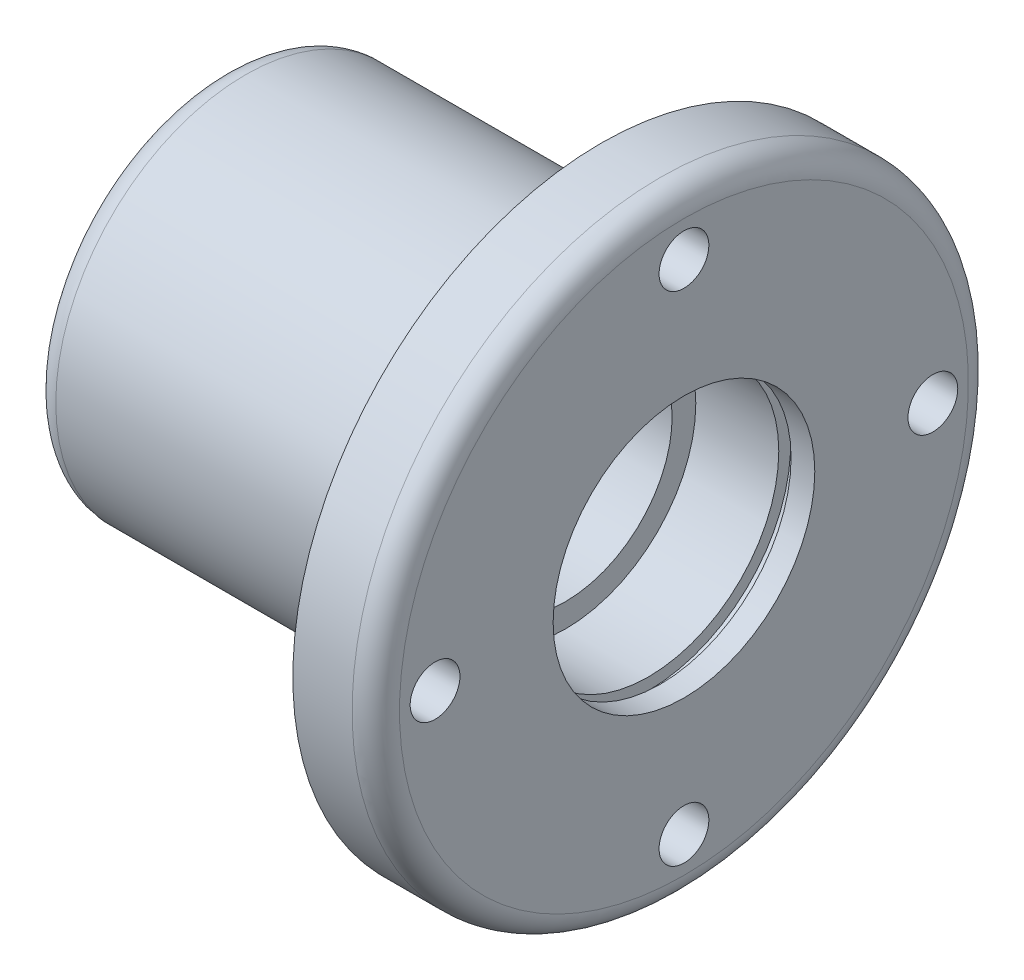
SolidWorks part; units mm, degrees
ref_plane "Front Plane" through (0, 0, 0) normal (0, 0, 1) x (1, 0, 0)
ref_plane "Top Plane" through (0, 0, 0) normal (0, 1, 0) x (1, 0, 0)
ref_plane "Right Plane" through (0, 0, 0) normal (1, 0, 0) x (0, 0, -1)
sketch "Sketch1" plane through (0, 0, 0) normal (0, 0, 1) x (1, 0, 0)
  line L0 (-70.7, 0) -> (74.7, 0) construction
  line L2 (-70.7, 11) -> (-68.7, 11)
  line L3 (-68.7, 11) -> (-68.7, 12)
  line L4 (-68.7, 12) -> (-67.7, 12)
  line L5 (-67.7, 12) -> (-67.7, 11)
  line L6 (-67.7, 11) -> (-60.7, 11)
  line L7 (-60.7, 11) -> (-60.7, 9)
  line L8 (-60.7, 9) -> (-41.7, 9)
  line L9 (-41.7, 9) -> (-41.7, 11)
  line L10 (-41.7, 11) -> (-34.7, 11)
  line L11 (-34.7, 11) -> (-34.7, 12)
  line L12 (-34.7, 12) -> (-33.7, 12)
  line L13 (-33.7, 12) -> (-33.7, 11.0385)
  line L14 (-33.7, 11.0385) -> (-31.7, 11.0385)
  line L15 (-31.7, 11.0385) -> (-31.7, 26)
  line L16 (-31.7, 26) -> (-38.7, 26)
  line L17 (-38.7, 26) -> (-38.7, 16)
  line L18 (-38.7, 16) -> (-70.7, 16)
  line L19 (-70.7, 16) -> (-70.7, 11)
  dimension "D2" = 1
  dimension "D3" = 1
  dimension "D4" = 7
  dimension "D5" = 9
  dimension "D6" = 19
  dimension "D7" = 7
  dimension "D8" = 2
  dimension "D9" = 26
  dimension "D10" = 7
  dimension "D11" = 32
  dimension "D12" = 2
  dimension "D13" = 16
  dimension "D14" = 11
revolve "Revolve1" add sketch "Sketch1" angle 360 about L0
sketch "Sketch2" plane through (-31.7, 0, 0) normal (1, 0, 0) x (0, 0, -1)
  circle A0 centre (0, 21) radius 2.1
  circle A1 centre (21, 0) radius 2.1
  circle A2 centre (0, -21) radius 2.1
  circle A3 centre (-21, 0) radius 2.1
  point P12 (0, 0)
  dimension "D1" = 4.2
  dimension "D2" = 21
  dimension "D3" = 4
extrude "Cut-Extrude1" cut sketch "Sketch2" against normal through all
fillet "Fillet1" radius 2 2 edges at (-31.7, -26, 0) (-70.7, -16, 0)
